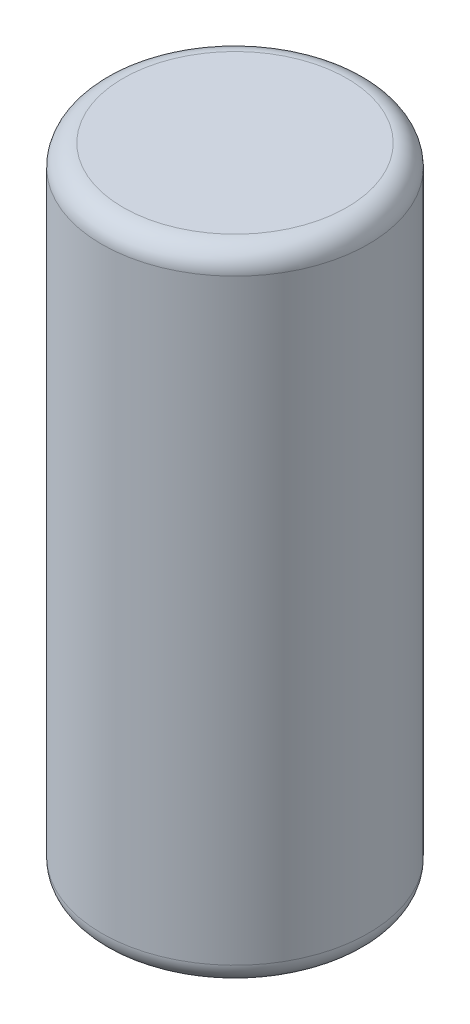
SolidWorks part; units mm, degrees
ref_plane "Front Plane" through (0, 0, 0) normal (0, 0, 1) x (1, 0, 0)
ref_plane "Top Plane" through (0, 0, 0) normal (0, 1, 0) x (1, 0, 0)
ref_plane "Right Plane" through (0, 0, 0) normal (1, 0, 0) x (0, 0, -1)
sketch "Sketch1" plane through (0, 0, 0) normal (0, 1, 0) x (1, 0, 0)
  circle A0 centre (0, 0) radius 62.5
  dimension "D1" = 125
extrude "Boss-Extrude1" add sketch "Sketch1" along normal blind 300
fillet "Fillet3" radius 10 2 edges at (0, 0, 62.5) (0, 300, 62.5)
